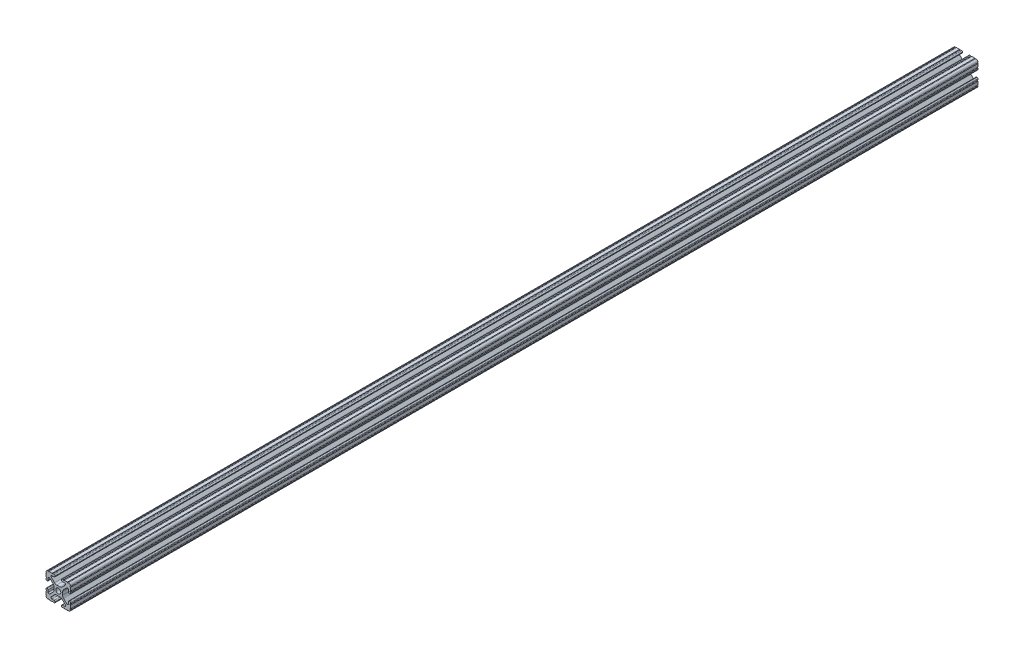
SolidWorks part; units mm, degrees
ref_plane "Front Plane" through (0, 0, 0) normal (0, 0, 1) x (1, 0, 0)
ref_plane "Top Plane" through (0, 0, 0) normal (0, 1, 0) x (1, 0, 0)
ref_plane "Right Plane" through (0, 0, 0) normal (1, 0, 0) x (0, 0, -1)
sketch "Sketch1" plane through (0, 0, 0) normal (0, 0, 1) x (1, 0, 0)
  line L88 (-7.1797, -8.6452) -> (-3.9523, -5.4237)
  line L89 (-1.7093, -4.4958) -> (1.7093, -4.4958)
  line L90 (3.9523, -5.4237) -> (7.1797, -8.6452)
  line L91 (6.4164, -10.4902) -> (4.2875, -10.4902)
  line L92 (3.2385, -11.5392) -> (3.2385, -11.651)
  line L93 (4.2875, -12.7) -> (5.3171, -12.7)
  line L94 (6.3331, -12.7) -> (9.5504, -12.7)
  line L95 (12.7, -9.5504) -> (12.7, -6.3331)
  line L96 (12.7, -5.3171) -> (12.7, -4.2875)
  line L97 (11.651, -3.2385) -> (11.5392, -3.2385)
  line L98 (10.4902, -4.2875) -> (10.4902, -6.4021)
  line L99 (8.7371, -7.1294) -> (5.441, -3.8408)
  line L100 (4.5085, -1.5932) -> (4.5085, 1.5932)
  line L101 (5.441, 3.8408) -> (8.7371, 7.1294)
  line L102 (10.4902, 6.4021) -> (10.4902, 4.2875)
  line L103 (11.5392, 3.2385) -> (11.651, 3.2385)
  line L104 (12.7, 4.2875) -> (12.7, 5.3171)
  line L105 (12.7, 6.3331) -> (12.7, 9.5504)
  line L106 (9.5504, 12.7) -> (6.3331, 12.7)
  line L107 (5.3171, 12.7) -> (4.2875, 12.7)
  line L108 (3.2385, 11.651) -> (3.2385, 11.5392)
  line L109 (4.2875, 10.4902) -> (6.4768, 10.4902)
  line L110 (7.207, 8.7244) -> (3.8983, 5.4232)
  line L111 (1.6558, 4.4958) -> (-1.6558, 4.4958)
  line L112 (-3.8983, 5.4232) -> (-7.207, 8.7244)
  line L113 (-6.4768, 10.4902) -> (-4.2875, 10.4902)
  line L114 (-3.2385, 11.5392) -> (-3.2385, 11.651)
  line L115 (-4.2875, 12.7) -> (-5.3171, 12.7)
  line L116 (-6.3331, 12.7) -> (-9.5504, 12.7)
  line L117 (-12.7, 9.5504) -> (-12.7, 6.3331)
  line L118 (-12.7, 5.3171) -> (-12.7, 4.2875)
  line L119 (-11.651, 3.2385) -> (-11.5392, 3.2385)
  line L120 (-10.4902, 4.2875) -> (-10.4902, 6.4021)
  line L121 (-8.7371, 7.1294) -> (-5.441, 3.8408)
  line L122 (-4.5085, 1.5932) -> (-4.5085, -1.5932)
  line L123 (-5.441, -3.8408) -> (-8.7371, -7.1294)
  line L124 (-10.4902, -6.4021) -> (-10.4902, -4.2875)
  line L125 (-11.5392, -3.2385) -> (-11.651, -3.2385)
  line L126 (-12.7, -4.2875) -> (-12.7, -5.3171)
  line L127 (-12.7, -6.3331) -> (-12.7, -9.5504)
  line L128 (-9.5504, -12.7) -> (-6.3331, -12.7)
  line L129 (-5.3171, -12.7) -> (-4.2875, -12.7)
  line L130 (-3.2385, -11.651) -> (-3.2385, -11.5392)
  line L131 (-4.2875, -10.4902) -> (-6.4164, -10.4902)
  circle A1 centre (0, 0) radius 2.6035
  arc A104 (-7.1797, -8.6452) -> (-6.4164, -10.4902) centre (-6.4164, -9.4098) ccw
  arc A105 (-1.7093, -4.4958) -> (-3.9523, -5.4237) centre (-1.7093, -7.6708) ccw
  arc A106 (3.9523, -5.4237) -> (1.7093, -4.4958) centre (1.7093, -7.6708) ccw
  arc A107 (6.4164, -10.4902) -> (7.1797, -8.6452) centre (6.4164, -9.4098) ccw
  arc A108 (4.2875, -10.4902) -> (3.2385, -11.5392) centre (4.2875, -11.5392) ccw
  arc A109 (3.2385, -11.651) -> (4.2875, -12.7) centre (4.2875, -11.651) ccw
  arc A110 (6.3331, -12.7) -> (5.3171, -12.7) centre (5.8251, -12.7) ccw
  arc A111 (10.5664, -12.6998) -> (9.5504, -12.7) centre (10.0584, -12.7) ccw
  arc A112 (10.5664, -12.6998) -> (12.6998, -10.5664) centre (10.5918, -10.5918) ccw
  arc A113 (12.7, -9.5504) -> (12.6998, -10.5664) centre (12.7, -10.0584) ccw
  arc A114 (12.7, -5.3171) -> (12.7, -6.3331) centre (12.7, -5.8251) ccw
  arc A115 (12.7, -4.2875) -> (11.651, -3.2385) centre (11.651, -4.2875) ccw
  arc A116 (11.5392, -3.2385) -> (10.4902, -4.2875) centre (11.5392, -4.2875) ccw
  arc A117 (8.7371, -7.1294) -> (10.4902, -6.4021) centre (9.4628, -6.4021) ccw
  arc A118 (4.5085, -1.5932) -> (5.441, -3.8408) centre (7.6835, -1.5932) ccw
  arc A119 (5.441, 3.8408) -> (4.5085, 1.5932) centre (7.6835, 1.5932) ccw
  arc A120 (10.4902, 6.4021) -> (8.7371, 7.1294) centre (9.4628, 6.4021) ccw
  arc A121 (10.4902, 4.2875) -> (11.5392, 3.2385) centre (11.5392, 4.2875) ccw
  arc A122 (11.651, 3.2385) -> (12.7, 4.2875) centre (11.651, 4.2875) ccw
  arc A123 (12.7, 6.3331) -> (12.7, 5.3171) centre (12.7, 5.8251) ccw
  arc A124 (12.6998, 10.5664) -> (12.7, 9.5504) centre (12.7, 10.0584) ccw
  arc A125 (12.6998, 10.5664) -> (10.5664, 12.6998) centre (10.5918, 10.5918) ccw
  arc A126 (9.5504, 12.7) -> (10.5664, 12.6998) centre (10.0584, 12.7) ccw
  arc A127 (5.3171, 12.7) -> (6.3331, 12.7) centre (5.8251, 12.7) ccw
  arc A128 (4.2875, 12.7) -> (3.2385, 11.651) centre (4.2875, 11.651) ccw
  arc A129 (3.2385, 11.5392) -> (4.2875, 10.4902) centre (4.2875, 11.5392) ccw
  arc A130 (7.207, 8.7244) -> (6.4768, 10.4902) centre (6.4768, 9.4563) ccw
  arc A131 (1.6558, 4.4958) -> (3.8983, 5.4232) centre (1.6558, 7.6708) ccw
  arc A132 (-3.8983, 5.4232) -> (-1.6558, 4.4958) centre (-1.6558, 7.6708) ccw
  arc A133 (-6.4768, 10.4902) -> (-7.207, 8.7244) centre (-6.4768, 9.4563) ccw
  arc A134 (-4.2875, 10.4902) -> (-3.2385, 11.5392) centre (-4.2875, 11.5392) ccw
  arc A135 (-3.2385, 11.651) -> (-4.2875, 12.7) centre (-4.2875, 11.651) ccw
  arc A136 (-6.3331, 12.7) -> (-5.3171, 12.7) centre (-5.8251, 12.7) ccw
  arc A137 (-10.5664, 12.6998) -> (-9.5504, 12.7) centre (-10.0584, 12.7) ccw
  arc A138 (-10.5664, 12.6998) -> (-12.6998, 10.5664) centre (-10.5918, 10.5918) ccw
  arc A139 (-12.7, 9.5504) -> (-12.6998, 10.5664) centre (-12.7, 10.0584) ccw
  arc A140 (-12.7, 5.3171) -> (-12.7, 6.3331) centre (-12.7, 5.8251) ccw
  arc A141 (-12.7, 4.2875) -> (-11.651, 3.2385) centre (-11.651, 4.2875) ccw
  arc A142 (-11.5392, 3.2385) -> (-10.4902, 4.2875) centre (-11.5392, 4.2875) ccw
  arc A143 (-8.7371, 7.1294) -> (-10.4902, 6.4021) centre (-9.4628, 6.4021) ccw
  arc A144 (-4.5085, 1.5932) -> (-5.441, 3.8408) centre (-7.6835, 1.5932) ccw
  arc A145 (-5.441, -3.8408) -> (-4.5085, -1.5932) centre (-7.6835, -1.5932) ccw
  arc A146 (-10.4902, -6.4021) -> (-8.7371, -7.1294) centre (-9.4628, -6.4021) ccw
  arc A147 (-10.4902, -4.2875) -> (-11.5392, -3.2385) centre (-11.5392, -4.2875) ccw
  arc A148 (-11.651, -3.2385) -> (-12.7, -4.2875) centre (-11.651, -4.2875) ccw
  arc A149 (-12.7, -6.3331) -> (-12.7, -5.3171) centre (-12.7, -5.8251) ccw
  arc A150 (-12.6998, -10.5664) -> (-12.7, -9.5504) centre (-12.7, -10.0584) ccw
  arc A151 (-12.6998, -10.5664) -> (-10.5664, -12.6998) centre (-10.5918, -10.5918) ccw
  arc A152 (-9.5504, -12.7) -> (-10.5664, -12.6998) centre (-10.0584, -12.7) ccw
  arc A153 (-5.3171, -12.7) -> (-6.3331, -12.7) centre (-5.8251, -12.7) ccw
  arc A154 (-4.2875, -12.7) -> (-3.2385, -11.651) centre (-4.2875, -11.651) ccw
  arc A155 (-3.2385, -11.5392) -> (-4.2875, -10.4902) centre (-4.2875, -11.5392) ccw
extrude "Boss-Extrude1" add sketch "Sketch1" along normal mid plane 939.8
